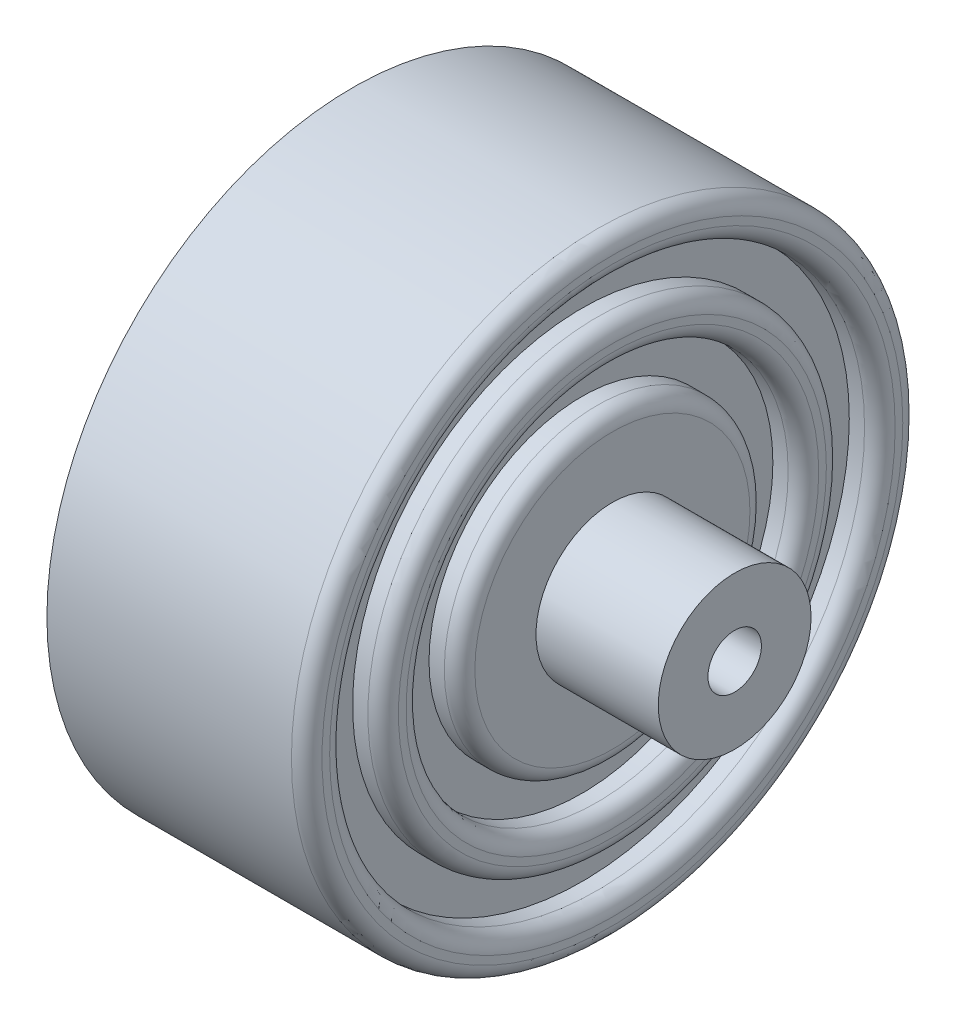
SolidWorks part; units mm, degrees
ref_plane "Front Plane" through (0, 0, 0) normal (0, 0, 1) x (1, 0, 0)
ref_plane "Top Plane" through (0, 0, 0) normal (0, 1, 0) x (1, 0, 0)
ref_plane "Right Plane" through (0, 0, 0) normal (1, 0, 0) x (0, 0, -1)
sketch "Sketch1" plane through (0, 0, 0) normal (1, 0, 0) x (0, 0, -1)
  circle A0 centre (0, 0) radius 20
  dimension "D1" = 40
extrude "Boss-Extrude1" add sketch "Sketch1" along normal blind 26
sketch "Sketch3" plane through (26, 0, 0) normal (1, 0, 0) x (0, 0, -1)
  circle A0 centre (0, 0) radius 20
  circle A1 centre (0, 0) radius 5
  dimension "D1" = 10
extrude "Cut-Extrude1" cut sketch "Sketch3" against normal blind 9
sketch "Sketch4" plane through (26, 0, 0) normal (1, 0, 0) x (0, 0, -1)
  circle A0 centre (0, 0) radius 1.75
  dimension "D1" = 3.5
extrude "Cut-Extrude2" cut sketch "Sketch4" against normal blind 15
sketch "Sketch7" plane through (0, 0, 0) normal (-1, 0, 0) x (0, 0, 1)
  line L2 (-18, 1.5) -> (-8.5188, 5.2374)
  line L3 (-18, -1.5) -> (-8.5188, -5.2374)
  line L4 (-1.5, 18) -> (-5.4225, 8.4022)
  line L5 (1.5, 18) -> (5.4225, 8.4022)
  line L6 (18, 1.5) -> (8.5188, 5.2374)
  line L7 (18, -1.5) -> (8.5188, -5.2374)
  line L8 (-1.5, -18) -> (-5.4225, -8.4022)
  line L9 (1.5, -18) -> (5.4225, -8.4022)
  arc A0 (5.4225, -8.4022) -> (8.5188, -5.2374) centre (0, 0) ccw
  arc A1 (1.5, 18) -> (-1.5, 18) centre (0, 18) ccw
  arc A2 (18, -1.5) -> (18, 1.5) centre (18, 0) ccw
  arc A3 (-1.5, -18) -> (1.5, -18) centre (0, -18) ccw
  arc A4 (-18, 1.5) -> (-18, -1.5) centre (-18, 0) ccw
  arc A9 (8.5188, 5.2374) -> (5.4225, 8.4022) centre (0, 0) ccw
  arc A10 (-5.4225, 8.4022) -> (-8.5188, 5.2374) centre (0, 0) ccw
  arc A11 (-8.5188, -5.2374) -> (-5.4225, -8.4022) centre (0, 0) ccw
  point P7 (0, 18)
  point P8 (18, 0)
  point P9 (0, -18)
  point P10 (-18, 0)
  dimension "D1" = 20
  dimension "D6" = 3
  dimension "D7" = 3
  dimension "D8" = 3
  dimension "D9" = 3
extrude "Cut-Extrude4" cut sketch "Sketch7" against normal blind 2
sketch "Sketch8" plane through (2, 0, 0) normal (-1, 0, 0) x (0, 0, 1)
  circle A0 centre (0, 0) radius 1.5
  dimension "D1" = 3
extrude "Cut-Extrude5" cut sketch "Sketch8" against normal through all
sketch "Sketch9" plane through (17, 0, 0) normal (1, 0, 0) x (0, 0, -1)
  circle A0 centre (0, 0) radius 17.5
  circle A1 centre (0, 0) radius 15
  circle A2 centre (0, 0) radius 12.5
  circle A3 centre (0, 0) radius 10
  dimension "D1" = 35
  dimension "D2" = 30
  dimension "D3" = 25
  dimension "D4" = 20
extrude "Cut-Extrude6" cut sketch "Sketch9" against normal blind 2 contours A0 A1 | A2 A3
fillet "Fillet1" radius 1 1 edges at (17, 0, -17.5)
fillet "Fillet2" radius 1 1 edges at (17, 0, -20)
fillet "Fillet3" radius 1 1 edges at (17, 0, -15)
fillet "Fillet4" radius 1 1 edges at (17, 0, -12.5)
fillet "Fillet5" radius 1 1 edges at (17, 0, -10)
sketch "Sketch10" plane through (26, 0, 0) normal (1, 0, 0) x (0, 0, -1)
  circle A1 centre (0, 0) radius 5
  circle A2 centre (0, 0) radius 5
  dimension "D1" = 0
extrude "Cut-Extrude7" cut sketch "Sketch10" against normal blind 1
